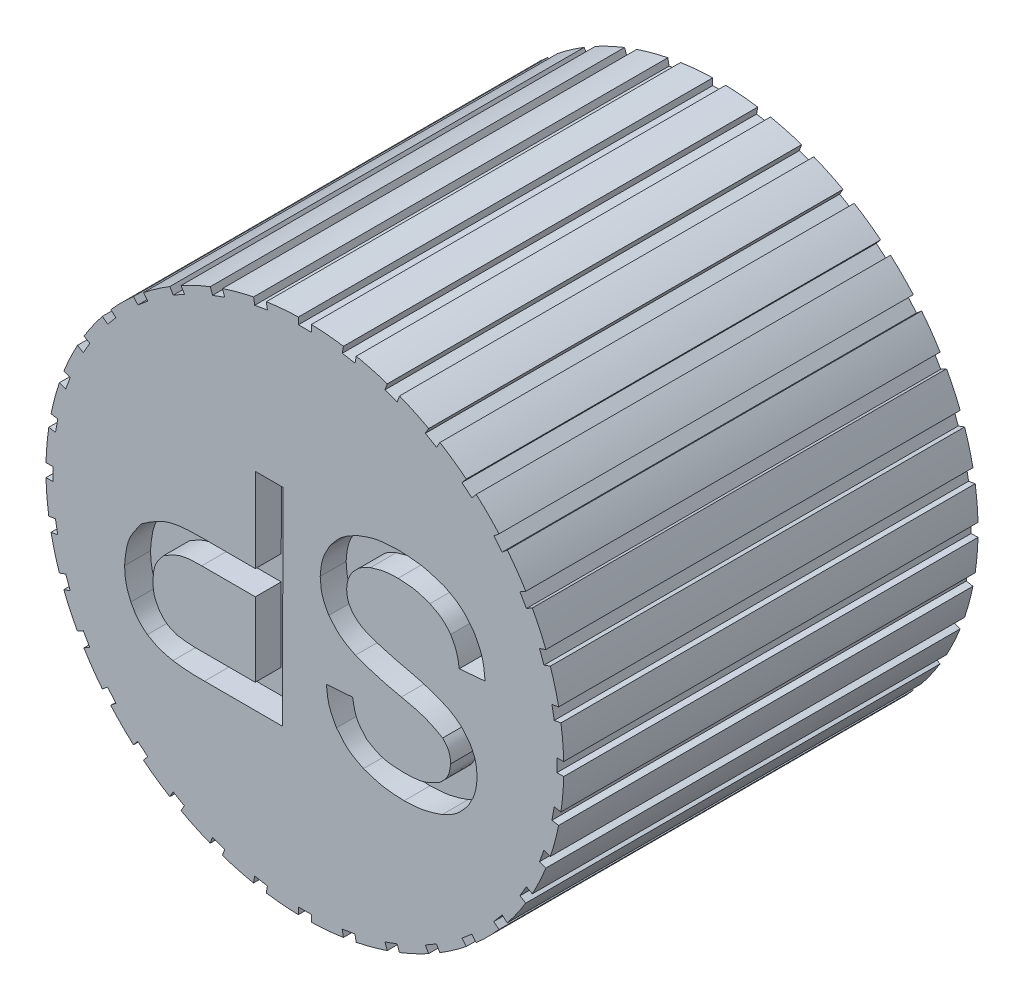
SolidWorks part; units mm, degrees
ref_plane "Front Plane" through (0, 0, 0) normal (0, 0, 1) x (1, 0, 0)
ref_plane "Top Plane" through (0, 0, 0) normal (0, 1, 0) x (1, 0, 0)
ref_plane "Right Plane" through (0, 0, 0) normal (1, 0, 0) x (0, 0, -1)
sketch "Sketch1" plane through (0, 0, 0) normal (0, 1, 0) x (1, 0, 0)
  line L0 (10, 0) -> (0, 0)
  line L1 (0, 0) -> (0, -16)
  line L2 (0, -16) -> (10, -16)
  line L3 (10, -16) -> (10, 0)
  line L4 (0, 0) -> (0, -16) construction
revolve "Revolve1" add sketch "Sketch1" angle 360 about L4
sketch "Sketch2" plane through (0, 0, 0) normal (0, 0, -1) x (-1, 0, 0)
  line L0 (3.183, 9.4799) -> (3.0936, 9.2344)
  line L1 (3.0936, 9.2344) -> (3.5632, 9.0635)
  line L2 (3.5632, 9.0635) -> (3.6526, 9.3091)
  arc A0 (3.6526, 9.3091) -> (3.183, 9.4799) centre (0, 0) ccw
extrude "Cut-Extrude1" cut sketch "Sketch2" against normal blind 16
sketch "Sketch3" plane through (0, 0, 0) normal (0, 0, -1) x (-1, 0, 0)
  line L0 (4.7808, 8.7832) -> (4.6502, 8.5569)
  line L1 (4.6502, 8.5569) -> (5.0829, 8.307)
  line L2 (5.0829, 8.307) -> (5.2136, 8.5334)
  arc A0 (5.2136, 8.5334) -> (4.7808, 8.7832) centre (0, 0) ccw
extrude "Cut-Extrude2" cut sketch "Sketch3" against normal blind 16
sketch "Sketch4" plane through (0, 0, 0) normal (0, 0, -1) x (-1, 0, 0)
  line L0 (6.2334, 7.8195) -> (6.0654, 7.6194)
  line L1 (6.0654, 7.6194) -> (6.4482, 7.2982)
  line L2 (6.4482, 7.2982) -> (6.6162, 7.4984)
  arc A0 (6.6162, 7.4984) -> (6.2334, 7.8195) centre (0, 0) ccw
extrude "Cut-Extrude3" cut sketch "Sketch4" against normal blind 16
sketch "Sketch5" plane through (0, 0, 0) normal (0, 0, -1) x (-1, 0, 0)
  line L0 (7.4965, 6.6183) -> (7.2963, 6.4504)
  line L1 (7.2963, 6.4504) -> (7.6176, 6.0676)
  line L2 (7.6176, 6.0676) -> (7.8178, 6.2356)
  arc A0 (7.8178, 6.2356) -> (7.4965, 6.6183) centre (0, 0) ccw
extrude "Cut-Extrude4" cut sketch "Sketch5" against normal blind 16
sketch "Sketch6" plane through (0, 0, 0) normal (0, 0, -1) x (-1, 0, 0)
  line L0 (8.5319, 5.216) -> (8.3056, 5.0854)
  line L1 (8.3056, 5.0854) -> (8.5554, 4.6526)
  line L2 (8.5554, 4.6526) -> (8.7818, 4.7833)
  arc A0 (8.7818, 4.7833) -> (8.5319, 5.216) centre (0, 0) ccw
extrude "Cut-Extrude5" cut sketch "Sketch6" against normal blind 16
sketch "Sketch7" plane through (0, 0, 0) normal (0, 0, -1) x (-1, 0, 0)
  line L0 (9.308, 3.6552) -> (9.0625, 3.5659)
  line L1 (9.0625, 3.5659) -> (9.2334, 3.0963)
  line L2 (9.2334, 3.0963) -> (9.479, 3.1857)
  arc A0 (9.479, 3.1857) -> (9.308, 3.6552) centre (0, 0) ccw
extrude "Cut-Extrude6" cut sketch "Sketch7" against normal blind 16
sketch "Sketch8" plane through (0, 0, 0) normal (0, 0, -1) x (-1, 0, 0)
  line L0 (9.8013, 1.9834) -> (9.544, 1.938)
  line L1 (9.544, 1.938) -> (9.6308, 1.4459)
  line L2 (9.6308, 1.4459) -> (9.8882, 1.4913)
  arc A0 (9.8882, 1.4913) -> (9.8013, 1.9834) centre (0, 0) ccw
extrude "Cut-Extrude7" cut sketch "Sketch8" against normal blind 16
sketch "Sketch9" plane through (0, 0, 0) normal (0, 0, -1) x (-1, 0, 0)
  line L0 (9.9968, 0.2513) -> (9.7356, 0.2513)
  line L1 (9.7356, 0.2513) -> (9.7356, -0.2484)
  line L2 (9.7356, -0.2484) -> (9.9969, -0.2484)
  arc A0 (9.9969, -0.2484) -> (9.9968, 0.2513) centre (0, 0) ccw
extrude "Cut-Extrude8" cut sketch "Sketch9" against normal blind 16
sketch "Sketch10" plane through (0, 0, 0) normal (0, 0, -1) x (-1, 0, 0)
  line L0 (9.8886, -1.4885) -> (9.6313, -1.4431)
  line L1 (9.6313, -1.4431) -> (9.5445, -1.9352)
  line L2 (9.5445, -1.9352) -> (9.8019, -1.9806)
  arc A0 (9.8019, -1.9806) -> (9.8886, -1.4885) centre (0, 0) ccw
extrude "Cut-Extrude9" cut sketch "Sketch10" against normal blind 16
sketch "Sketch11" plane through (0, 0, 0) normal (0, 0, -1) x (-1, 0, 0)
  line L0 (9.4799, -3.183) -> (9.2344, -3.0936)
  line L1 (9.2344, -3.0936) -> (9.0635, -3.5632)
  line L2 (9.0635, -3.5632) -> (9.3091, -3.6526)
  arc A0 (9.3091, -3.6526) -> (9.4799, -3.183) centre (0, 0) ccw
extrude "Cut-Extrude10" cut sketch "Sketch11" against normal blind 16
sketch "Sketch12" plane through (0, 0, 0) normal (0, 0, -1) x (-1, 0, 0)
  line L0 (8.7832, -4.7808) -> (8.5569, -4.6502)
  line L1 (8.5569, -4.6502) -> (8.307, -5.0829)
  line L2 (8.307, -5.0829) -> (8.5334, -5.2136)
  arc A0 (8.5334, -5.2136) -> (8.7832, -4.7808) centre (0, 0) ccw
extrude "Cut-Extrude11" cut sketch "Sketch12" against normal blind 16
sketch "Sketch13" plane through (0, 0, 0) normal (0, 0, -1) x (-1, 0, 0)
  line L0 (7.8195, -6.2334) -> (7.6194, -6.0654)
  line L1 (7.6194, -6.0654) -> (7.2982, -6.4482)
  line L2 (7.2982, -6.4482) -> (7.4984, -6.6162)
  arc A0 (7.4984, -6.6162) -> (7.8195, -6.2334) centre (0, 0) ccw
extrude "Cut-Extrude12" cut sketch "Sketch13" against normal blind 16
sketch "Sketch14" plane through (0, 0, 0) normal (0, 0, -1) x (-1, 0, 0)
  line L0 (6.6183, -7.4965) -> (6.4504, -7.2963)
  line L1 (6.4504, -7.2963) -> (6.0676, -7.6176)
  line L2 (6.0676, -7.6176) -> (6.2356, -7.8178)
  arc A0 (6.2356, -7.8178) -> (6.6183, -7.4965) centre (0, 0) ccw
extrude "Cut-Extrude13" cut sketch "Sketch14" against normal blind 16
sketch "Sketch15" plane through (0, 0, 0) normal (0, 0, -1) x (-1, 0, 0)
  line L0 (5.216, -8.5319) -> (5.0854, -8.3056)
  line L1 (5.0854, -8.3056) -> (4.6526, -8.5554)
  line L2 (4.6526, -8.5554) -> (4.7833, -8.7818)
  arc A0 (4.7833, -8.7818) -> (5.216, -8.5319) centre (0, 0) ccw
extrude "Cut-Extrude14" cut sketch "Sketch15" against normal blind 16
sketch "Sketch16" plane through (0, 0, 0) normal (0, 0, -1) x (-1, 0, 0)
  line L0 (3.6552, -9.308) -> (3.5659, -9.0625)
  line L1 (3.5659, -9.0625) -> (3.0963, -9.2334)
  line L2 (3.0963, -9.2334) -> (3.1857, -9.479)
  arc A0 (3.1857, -9.479) -> (3.6552, -9.308) centre (0, 0) ccw
extrude "Cut-Extrude15" cut sketch "Sketch16" against normal blind 16
sketch "Sketch17" plane through (0, 0, 0) normal (0, 0, -1) x (-1, 0, 0)
  line L0 (1.9834, -9.8013) -> (1.938, -9.544)
  line L1 (1.938, -9.544) -> (1.4459, -9.6308)
  line L2 (1.4459, -9.6308) -> (1.4913, -9.8882)
  arc A0 (1.4913, -9.8882) -> (1.9834, -9.8013) centre (0, 0) ccw
extrude "Cut-Extrude16" cut sketch "Sketch17" against normal blind 16
sketch "Sketch18" plane through (0, 0, 0) normal (0, 0, -1) x (-1, 0, 0)
  line L0 (0.2513, -9.9968) -> (0.2513, -9.7356)
  line L1 (0.2513, -9.7356) -> (-0.2484, -9.7356)
  line L2 (-0.2484, -9.7356) -> (-0.2484, -9.9969)
  arc A0 (-0.2484, -9.9969) -> (0.2513, -9.9968) centre (0, 0) ccw
extrude "Cut-Extrude17" cut sketch "Sketch18" against normal blind 16
sketch "Sketch19" plane through (0, 0, 0) normal (0, 0, -1) x (-1, 0, 0)
  line L0 (-1.4885, -9.8886) -> (-1.4431, -9.6313)
  line L1 (-1.4431, -9.6313) -> (-1.9352, -9.5445)
  line L2 (-1.9352, -9.5445) -> (-1.9806, -9.8019)
  arc A0 (-1.9806, -9.8019) -> (-1.4885, -9.8886) centre (0, 0) ccw
extrude "Cut-Extrude18" cut sketch "Sketch19" against normal blind 16
sketch "Sketch20" plane through (0, 0, 0) normal (0, 0, -1) x (-1, 0, 0)
  line L0 (-3.183, -9.4799) -> (-3.0936, -9.2344)
  line L1 (-3.0936, -9.2344) -> (-3.5632, -9.0635)
  line L2 (-3.5632, -9.0635) -> (-3.6526, -9.3091)
  arc A0 (-3.6526, -9.3091) -> (-3.183, -9.4799) centre (0, 0) ccw
extrude "Cut-Extrude19" cut sketch "Sketch20" against normal blind 16
sketch "Sketch21" plane through (0, 0, 0) normal (0, 0, -1) x (-1, 0, 0)
  line L0 (-4.7808, -8.7832) -> (-4.6502, -8.5569)
  line L1 (-4.6502, -8.5569) -> (-5.0829, -8.307)
  line L2 (-5.0829, -8.307) -> (-5.2136, -8.5334)
  arc A0 (-5.2136, -8.5334) -> (-4.7808, -8.7832) centre (0, 0) ccw
extrude "Cut-Extrude20" cut sketch "Sketch21" against normal blind 16
sketch "Sketch22" plane through (0, 0, 0) normal (0, 0, -1) x (-1, 0, 0)
  line L0 (-6.2334, -7.8195) -> (-6.0654, -7.6194)
  line L1 (-6.0654, -7.6194) -> (-6.4482, -7.2982)
  line L2 (-6.4482, -7.2982) -> (-6.6162, -7.4984)
  arc A0 (-6.6162, -7.4984) -> (-6.2334, -7.8195) centre (0, 0) ccw
extrude "Cut-Extrude21" cut sketch "Sketch22" against normal blind 16
sketch "Sketch23" plane through (0, 0, 0) normal (0, 0, -1) x (-1, 0, 0)
  line L0 (-7.4965, -6.6183) -> (-7.2963, -6.4504)
  line L1 (-7.2963, -6.4504) -> (-7.6176, -6.0676)
  line L2 (-7.6176, -6.0676) -> (-7.8178, -6.2356)
  arc A0 (-7.8178, -6.2356) -> (-7.4965, -6.6183) centre (0, 0) ccw
extrude "Cut-Extrude22" cut sketch "Sketch23" against normal blind 16
sketch "Sketch24" plane through (0, 0, 0) normal (0, 0, -1) x (-1, 0, 0)
  line L0 (-8.5319, -5.216) -> (-8.3056, -5.0854)
  line L1 (-8.3056, -5.0854) -> (-8.5554, -4.6526)
  line L2 (-8.5554, -4.6526) -> (-8.7818, -4.7833)
  arc A0 (-8.7818, -4.7833) -> (-8.5319, -5.216) centre (0, 0) ccw
extrude "Cut-Extrude23" cut sketch "Sketch24" against normal blind 16
sketch "Sketch25" plane through (0, 0, 0) normal (0, 0, -1) x (-1, 0, 0)
  line L0 (-9.308, -3.6552) -> (-9.0625, -3.5659)
  line L1 (-9.0625, -3.5659) -> (-9.2334, -3.0963)
  line L2 (-9.2334, -3.0963) -> (-9.479, -3.1857)
  arc A0 (-9.479, -3.1857) -> (-9.308, -3.6552) centre (0, 0) ccw
extrude "Cut-Extrude24" cut sketch "Sketch25" against normal blind 16
sketch "Sketch26" plane through (0, 0, 0) normal (0, 0, -1) x (-1, 0, 0)
  line L0 (-9.8013, -1.9834) -> (-9.544, -1.938)
  line L1 (-9.544, -1.938) -> (-9.6308, -1.4459)
  line L2 (-9.6308, -1.4459) -> (-9.8882, -1.4913)
  arc A0 (-9.8882, -1.4913) -> (-9.8013, -1.9834) centre (0, 0) ccw
extrude "Cut-Extrude25" cut sketch "Sketch26" against normal blind 16
sketch "Sketch27" plane through (0, 0, 0) normal (0, 0, -1) x (-1, 0, 0)
  line L0 (-9.9968, -0.2513) -> (-9.7356, -0.2513)
  line L1 (-9.7356, -0.2513) -> (-9.7356, 0.2484)
  line L2 (-9.7356, 0.2484) -> (-9.9969, 0.2484)
  arc A0 (-9.9969, 0.2484) -> (-9.9968, -0.2513) centre (0, 0) ccw
extrude "Cut-Extrude26" cut sketch "Sketch27" against normal blind 16
sketch "Sketch28" plane through (0, 0, 0) normal (0, 0, -1) x (-1, 0, 0)
  line L0 (-9.8886, 1.4885) -> (-9.6313, 1.4431)
  line L1 (-9.6313, 1.4431) -> (-9.5445, 1.9352)
  line L2 (-9.5445, 1.9352) -> (-9.8019, 1.9806)
  arc A0 (-9.8019, 1.9806) -> (-9.8886, 1.4885) centre (0, 0) ccw
extrude "Cut-Extrude27" cut sketch "Sketch28" against normal blind 16
sketch "Sketch29" plane through (0, 0, 0) normal (0, 0, -1) x (-1, 0, 0)
  line L0 (-9.4799, 3.183) -> (-9.2344, 3.0936)
  line L1 (-9.2344, 3.0936) -> (-9.0635, 3.5632)
  line L2 (-9.0635, 3.5632) -> (-9.3091, 3.6526)
  arc A0 (-9.3091, 3.6526) -> (-9.4799, 3.183) centre (0, 0) ccw
extrude "Cut-Extrude28" cut sketch "Sketch29" against normal blind 16
sketch "Sketch30" plane through (0, 0, 0) normal (0, 0, -1) x (-1, 0, 0)
  line L0 (-8.7832, 4.7808) -> (-8.5569, 4.6502)
  line L1 (-8.5569, 4.6502) -> (-8.307, 5.0829)
  line L2 (-8.307, 5.0829) -> (-8.5334, 5.2136)
  arc A0 (-8.5334, 5.2136) -> (-8.7832, 4.7808) centre (0, 0) ccw
extrude "Cut-Extrude29" cut sketch "Sketch30" against normal blind 16
sketch "Sketch31" plane through (0, 0, 0) normal (0, 0, -1) x (-1, 0, 0)
  line L0 (-7.8195, 6.2334) -> (-7.6194, 6.0654)
  line L1 (-7.6194, 6.0654) -> (-7.2982, 6.4482)
  line L2 (-7.2982, 6.4482) -> (-7.4984, 6.6162)
  arc A0 (-7.4984, 6.6162) -> (-7.8195, 6.2334) centre (0, 0) ccw
extrude "Cut-Extrude30" cut sketch "Sketch31" against normal blind 16
sketch "Sketch32" plane through (0, 0, 0) normal (0, 0, -1) x (-1, 0, 0)
  line L0 (-6.6183, 7.4965) -> (-6.4504, 7.2963)
  line L1 (-6.4504, 7.2963) -> (-6.0676, 7.6176)
  line L2 (-6.0676, 7.6176) -> (-6.2356, 7.8178)
  arc A0 (-6.2356, 7.8178) -> (-6.6183, 7.4965) centre (0, 0) ccw
extrude "Cut-Extrude31" cut sketch "Sketch32" against normal blind 16
sketch "Sketch33" plane through (0, 0, 0) normal (0, 0, -1) x (-1, 0, 0)
  line L0 (-5.216, 8.5319) -> (-5.0854, 8.3056)
  line L1 (-5.0854, 8.3056) -> (-4.6526, 8.5554)
  line L2 (-4.6526, 8.5554) -> (-4.7833, 8.7818)
  arc A0 (-4.7833, 8.7818) -> (-5.216, 8.5319) centre (0, 0) ccw
extrude "Cut-Extrude32" cut sketch "Sketch33" against normal blind 16
sketch "Sketch34" plane through (0, 0, 0) normal (0, 0, -1) x (-1, 0, 0)
  line L0 (-3.6552, 9.308) -> (-3.5659, 9.0625)
  line L1 (-3.5659, 9.0625) -> (-3.0963, 9.2334)
  line L2 (-3.0963, 9.2334) -> (-3.1857, 9.479)
  arc A0 (-3.1857, 9.479) -> (-3.6552, 9.308) centre (0, 0) ccw
extrude "Cut-Extrude33" cut sketch "Sketch34" against normal blind 16
sketch "Sketch35" plane through (0, 0, 0) normal (0, 0, -1) x (-1, 0, 0)
  line L0 (-1.9834, 9.8013) -> (-1.938, 9.544)
  line L1 (-1.938, 9.544) -> (-1.4459, 9.6308)
  line L2 (-1.4459, 9.6308) -> (-1.4913, 9.8882)
  arc A0 (-1.4913, 9.8882) -> (-1.9834, 9.8013) centre (0, 0) ccw
extrude "Cut-Extrude34" cut sketch "Sketch35" against normal blind 16
sketch "Sketch36" plane through (0, 0, 0) normal (0, 0, -1) x (-1, 0, 0)
  line L0 (-0.2513, 9.9968) -> (-0.2513, 9.7356)
  line L1 (-0.2513, 9.7356) -> (0.2484, 9.7356)
  line L2 (0.2484, 9.7356) -> (0.2484, 9.9969)
  arc A0 (0.2484, 9.9969) -> (-0.2513, 9.9968) centre (0, 0) ccw
extrude "Cut-Extrude35" cut sketch "Sketch36" against normal blind 16
sketch "Sketch37" plane through (0, 0, 0) normal (0, 0, -1) x (-1, 0, 0)
  line L0 (1.4885, 9.8886) -> (1.4431, 9.6313)
  line L1 (1.4431, 9.6313) -> (1.9352, 9.5445)
  line L2 (1.9352, 9.5445) -> (1.9806, 9.8019)
  arc A0 (1.9806, 9.8019) -> (1.4885, 9.8886) centre (0, 0) ccw
extrude "Cut-Extrude36" cut sketch "Sketch37" against normal blind 16
hole_wizard "Ø6.0 (6) Diameter Hole1" positions "Sketch39" profile "Sketch38" hole size "Ø6.0" standard "ANSI Metric"
sketch "Sketch39" plane through (0, 0, 0) normal (0, 0, -1) x (-1, 0, 0)
  point P0 (0, 0)
sketch "Sketch38" plane through (0, 0, 0) normal (1, 0, 0) x (0, 1, 0)
  line L0 (0, 0) -> (0, 14)
  line L1 (0, 14) -> (3, 14)
  line L2 (3, 14) -> (3, 0)
  line L5 (3, 0) -> (0, 0)
  line L10 (0, 14) -> (-3, 14) construction
  line L11 (0, -6.35) -> (0, 107.95) construction
  dimension "Hole Dia." = 6
  dimension "Hole Depth" = 14
  dimension "Drill Angle" = 180
sketch "Sketch40" plane through (0, 0, 14) normal (0, 0, -1) x (-1, 0, 0)
  line L0 (1.9843, 2.25) -> (-1.9843, 2.25)
  arc A0 (-1.9843, 2.25) -> (1.9843, 2.25) centre (0, 0) cw
extrude "Boss-Extrude1" add sketch "Sketch40" along normal blind 11.5
ref_plane "Plane1" through (0, 0, 13) normal (0, 0, 1) x (1, 0, 0)
sketch "Sketch41" plane through (0, 0, 13) normal (0, 0, 1) x (1, 0, 0)
  line L0 (-0.8576, -3.9992) -> (-3.8753, -3.9965)
  line L1 (-3.9639, 0.7512) -> (-1.912, 0.7493)
  line L2 (-1.912, 0.7493) -> (-1.9091, 4.0017)
  line L3 (-1.9091, 4.0017) -> (-0.8504, 4.0008)
  line L4 (-0.8504, 4.0008) -> (-0.8576, -3.9992)
  arc A0 (-3.8753, -3.9965) -> (-5.0922, -3.919) centre (-4.0199, 3.3272) cw
  spline S0 degree 3 poles (-5.0922, -3.919) (-5.1616, -3.9049) (-5.3004, -3.8767) (-5.5066, -3.8244) (-5.7064, -3.7501) (-5.8958, -3.6521) (-6.0183, -3.5803) (-6.0796, -3.5443) knots 0 0 0 0 0.199818 0.399437 0.599469 0.799548 1 1 1 1
  spline S1 degree 3 poles (-6.0796, -3.5443) (-6.1086, -3.5207) (-6.1667, -3.4734) (-6.2524, -3.4009) (-6.3352, -3.325) (-6.4137, -3.2443) (-6.4854, -3.1572) (-6.5502, -3.0647) (-6.6097, -2.9687) (-6.6658, -2.8706) (-6.702, -2.8046) (-6.7201, -2.7716) knots 0 0 0 0 0.110867 0.221625 0.332283 0.443112 0.554485 0.665741 0.777135 0.888564 1 1 1 1
  spline S2 degree 3 poles (-6.7201, -2.7716) (-6.7487, -2.7023) (-6.8058, -2.5636) (-6.8806, -2.351) (-6.929, -2.1304) (-6.9512, -1.9055) (-6.9584, -1.7552) (-6.9619, -1.68) knots 0 0 0 0 0.199722 0.399196 0.599258 0.799452 1 1 1 1
  spline S3 degree 3 poles (-6.9619, -1.68) (-6.955, -1.59) (-6.941, -1.4104) (-6.9087, -1.1429) (-6.8531, -0.8799) (-6.7591, -0.6274) (-6.627, -0.392) (-6.4739, -0.1691) (-6.3653, -0.0253) (-6.311, 0.0466) knots 0 0 0 0 0.143507 0.2866 0.428442 0.570098 0.713348 0.856629 1 1 1 1
  spline S4 degree 3 poles (-6.311, 0.0466) (-6.2341, 0.1) (-6.0804, 0.2069) (-5.8446, 0.3596) (-5.599, 0.4948) (-5.3415, 0.6024) (-5.0734, 0.6736) (-4.7996, 0.7162) (-4.5222, 0.7387) (-4.2432, 0.7482) (-4.057, 0.7502) (-3.9639, 0.7512) knots 0 0 0 0 0.111905 0.223719 0.335717 0.446572 0.556279 0.666369 0.777426 0.888707 1 1 1 1
extrude "Cut-Extrude37" cut sketch "Sketch41" against normal blind 1 from surface at 3 starting at face at (0, 0, 16)
ref_plane "Plane2" through (0, 0, 18) normal (0, 0, -1) x (0, 1, 0)
sketch "Sketch42" plane through (0, 0, 18) normal (0, 0, -1) x (0, 1, 0)
  line L0 (-3.0524, -3.9618) -> (-3.0542, -1.9154)
  line L1 (-3.0542, -1.9154) -> (-0.1947, -1.9129)
  line L2 (-0.1947, -1.9129) -> (-0.1929, -3.9811)
  arc A0 (-2.9806, -4.9495) -> (-3.0524, -3.9618) centre (1.5318, -4.1249) cw
  spline S0 degree 3 poles (-2.5079, -5.6175) (-2.5509, -5.5817) (-2.6366, -5.5102) (-2.7565, -5.3938) (-2.853, -5.2575) (-2.9226, -5.1061) (-2.9612, -5.0018) (-2.9806, -4.9495) knots 0 0 0 0 0.201652 0.401782 0.599697 0.799039 1 1 1 1
  spline S1 degree 3 poles (-0.1929, -3.9811) (-0.1935, -4.038) (-0.1946, -4.152) (-0.1998, -4.3227) (-0.2123, -4.4925) (-0.2357, -4.6604) (-0.2742, -4.8251) (-0.3319, -4.985) (-0.4044, -5.1397) (-0.4868, -5.2902) (-0.5446, -5.389) (-0.5736, -5.4384) knots 0 0 0 0 0.111441 0.222872 0.33409 0.444372 0.554109 0.664377 0.776028 0.888003 1 1 1 1
  spline S2 degree 3 poles (-0.5736, -5.4384) (-0.6071, -5.4674) (-0.674, -5.5252) (-0.7772, -5.6089) (-0.8853, -5.6855) (-1.0004, -5.7508) (-1.1239, -5.7987) (-1.2527, -5.8299) (-1.3839, -5.8496) (-1.5159, -5.8619) (-1.6041, -5.8676) (-1.6482, -5.8705) knots 0 0 0 0 0.111394 0.222725 0.334165 0.444661 0.554941 0.66642 0.777581 0.888729 1 1 1 1
  spline S3 degree 3 poles (-1.6482, -5.8705) (-1.682, -5.8686) (-1.7495, -5.8649) (-1.8505, -5.8572) (-1.9509, -5.8451) (-2.0498, -5.8265) (-2.1464, -5.7988) (-2.2399, -5.7612) (-2.3309, -5.7169) (-2.42, -5.6683) (-2.4786, -5.6344) (-2.5079, -5.6175) knots 0 0 0 0 0.111519 0.223027 0.33434 0.444774 0.554758 0.665246 0.776716 0.88835 1 1 1 1
extrude "Boss-Extrude2" add sketch "Sketch42" against normal blind 1 from surface at 3 starting at face at (-3.9973, -0.7319, 15)
sketch "Sketch43" plane through (0, 0, 13) normal (0, 0, 1) x (1, 0, 0)
  line L0 (0.8306, -1.747) -> (1.8457, -1.6715)
  line L1 (6.9617, 1.4235) -> (5.963, 1.3371)
  arc A0 (2.5518, 0.6962) -> (3.9757, 0.3048) centre (7.0683, 14.3396) ccw
  arc A1 (3.9757, 0.3048) -> (5.5196, -0.1959) centre (2.4936, -6.8957) cw
  arc A2 (3.7265, -0.7264) -> (1.9562, -0.2146) centre (5.8003, 9.7643) cw
  spline S0 degree 3 poles (5.963, 1.3371) (5.9526, 1.4061) (5.9319, 1.544) (5.8904, 1.7493) (5.8256, 1.9491) (5.735, 2.1386) (5.6675, 2.2611) (5.6337, 2.3224) knots 0 0 0 0 0.199817 0.399408 0.599425 0.799489 1 1 1 1
  spline S1 degree 3 poles (5.6337, 2.3224) (5.6094, 2.3516) (5.5608, 2.41) (5.486, 2.496) (5.4075, 2.5786) (5.3235, 2.6562) (5.2322, 2.7256) (5.1354, 2.7873) (5.0352, 2.8432) (4.9328, 2.8952) (4.8638, 2.9285) (4.8294, 2.9452) knots 0 0 0 0 0.11079 0.22144 0.331965 0.442711 0.554155 0.665473 0.776952 0.888472 1 1 1 1
  spline S2 degree 3 poles (4.8294, 2.9452) (4.7856, 2.9611) (4.6981, 2.9928) (4.5662, 3.0384) (4.433, 3.0798) (4.2977, 3.115) (4.1602, 3.1413) (4.0212, 3.159) (3.8817, 3.1706) (3.7418, 3.1782) (3.6484, 3.1818) (3.6018, 3.1837) knots 0 0 0 0 0.110954 0.221835 0.332653 0.443579 0.554858 0.666067 0.777362 0.888679 1 1 1 1
  spline S3 degree 3 poles (3.6018, 3.1837) (3.5614, 3.1825) (3.4808, 3.1801) (3.3599, 3.175) (3.2392, 3.1667) (3.1188, 3.1538) (2.9992, 3.1344) (2.8808, 3.1078) (2.7638, 3.0762) (2.6476, 3.0412) (2.5706, 3.0168) (2.532, 3.0045) knots 0 0 0 0 0.11102 0.22199 0.332916 0.443916 0.555146 0.666287 0.77751 0.888753 1 1 1 1
  spline S4 degree 3 poles (2.532, 3.0045) (2.4792, 2.9817) (2.3737, 2.9359) (2.2199, 2.8577) (2.0786, 2.7588) (1.9554, 2.6389) (1.8793, 2.5539) (1.8413, 2.5113) knots 0 0 0 0 0.20097 0.401435 0.601625 0.800606 1 1 1 1
  spline S5 degree 3 poles (1.8413, 2.5113) (1.8269, 2.4882) (1.7981, 2.442) (1.7564, 2.3717) (1.7181, 2.2997) (1.6849, 2.2256) (1.6593, 2.1488) (1.6415, 2.0696) (1.6293, 1.9892) (1.6208, 1.908) (1.6164, 1.8538) (1.6142, 1.8267) knots 0 0 0 0 0.111566 0.223105 0.334646 0.445332 0.555378 0.665775 0.777052 0.88852 1 1 1 1
  spline S6 degree 3 poles (1.6142, 1.8267) (1.616, 1.8005) (1.6196, 1.7482) (1.6269, 1.6699) (1.6378, 1.5922) (1.6544, 1.5157) (1.6787, 1.4416) (1.7109, 1.3706) (1.7484, 1.3019) (1.7893, 1.2349) (1.8177, 1.1909) (1.8319, 1.1689) knots 0 0 0 0 0.111558 0.223072 0.33467 0.445561 0.555613 0.665938 0.777161 0.888574 1 1 1 1
  spline S7 degree 3 poles (1.8319, 1.1689) (1.8545, 1.1461) (1.8998, 1.1005) (1.9692, 1.0336) (2.0414, 0.9698) (2.1178, 0.9106) (2.1994, 0.8585) (2.2849, 0.8124) (2.3727, 0.7711) (2.4619, 0.7329) (2.5218, 0.7084) (2.5518, 0.6962) knots 0 0 0 0 0.110793 0.221445 0.331976 0.442716 0.554139 0.665488 0.776967 0.88848 1 1 1 1
  spline S8 degree 3 poles (5.5196, -0.1959) (5.5563, -0.2172) (5.6295, -0.2595) (5.7383, -0.325) (5.8446, -0.3944) (5.9471, -0.4697) (6.0438, -0.5527) (6.1329, -0.6439) (6.2163, -0.7404) (6.2956, -0.8402) (6.3472, -0.9078) (6.373, -0.9416) knots 0 0 0 0 0.110936 0.221777 0.332532 0.443436 0.554783 0.665934 0.777258 0.888625 1 1 1 1
  spline S9 degree 3 poles (6.373, -0.9416) (6.4058, -1.0034) (6.4714, -1.1267) (6.5578, -1.3179) (6.6142, -1.5202) (6.6403, -1.7284) (6.6488, -1.8679) (6.6531, -1.9378) knots 0 0 0 0 0.200442 0.400254 0.599543 0.799433 1 1 1 1
  spline S10 degree 3 poles (6.6531, -1.9378) (6.6471, -2.0176) (6.6351, -2.177) (6.6012, -2.4147) (6.5308, -2.6446) (6.4264, -2.8608) (6.3477, -3) (6.3083, -3.0698) knots 0 0 0 0 0.200463 0.400277 0.599557 0.799395 1 1 1 1
  spline S11 degree 3 poles (6.3083, -3.0698) (6.2783, -3.1078) (6.2182, -3.1837) (6.1256, -3.2956) (6.0283, -3.4027) (5.9243, -3.5025) (5.8112, -3.5914) (5.6903, -3.6697) (5.564, -3.7404) (5.4344, -3.8057) (5.3471, -3.8474) (5.3035, -3.8683) knots 0 0 0 0 0.111631 0.223251 0.334625 0.44507 0.555082 0.665557 0.776902 0.888446 1 1 1 1
  spline S12 degree 3 poles (5.3035, -3.8683) (5.251, -3.8864) (5.146, -3.9226) (4.9877, -3.9746) (4.828, -4.0218) (4.6661, -4.0619) (4.5018, -4.0918) (4.3358, -4.112) (4.1693, -4.1252) (4.0023, -4.1337) (3.891, -4.1378) (3.8353, -4.1399) knots 0 0 0 0 0.110969 0.221873 0.33272 0.443664 0.554927 0.666125 0.777402 0.888699 1 1 1 1
  spline S13 degree 3 poles (3.8353, -4.1399) (3.776, -4.1378) (3.6573, -4.1337) (3.4795, -4.1252) (3.302, -4.1117) (3.125, -4.0908) (2.9494, -4.0595) (2.776, -4.0168) (2.6049, -3.9662) (2.4353, -3.9104) (2.3229, -3.8714) (2.2667, -3.852) knots 0 0 0 0 0.111007 0.221956 0.332855 0.443841 0.555089 0.666232 0.777471 0.888733 1 1 1 1
  spline S14 degree 3 poles (2.2667, -3.852) (2.2213, -3.8296) (2.1305, -3.7849) (1.9959, -3.715) (1.8646, -3.6397) (1.7388, -3.5565) (1.6213, -3.4624) (1.5133, -3.3573) (1.4122, -3.2448) (1.316, -3.1274) (1.2536, -3.0477) (1.2224, -3.0079) knots 0 0 0 0 0.11152 0.223024 0.334429 0.445018 0.555115 0.665589 0.776922 0.888456 1 1 1 1
  spline S15 degree 3 poles (1.2224, -3.0079) (1.179, -2.93) (1.0924, -2.7743) (0.9772, -2.533) (0.8984, -2.2771) (0.8565, -2.0131) (0.8393, -1.8358) (0.8306, -1.747) knots 0 0 0 0 0.200478 0.400337 0.599651 0.799529 1 1 1 1
  spline S16 degree 3 poles (1.8457, -1.6715) (1.8535, -1.7192) (1.869, -1.8145) (1.8958, -1.9567) (1.9301, -2.0976) (1.9754, -2.2353) (2.0365, -2.3667) (2.1146, -2.4887) (2.2036, -2.603) (2.2996, -2.7119) (2.3656, -2.7826) (2.3986, -2.818) knots 0 0 0 0 0.111175 0.222233 0.333273 0.444721 0.555342 0.66595 0.777329 0.888641 1 1 1 1
  spline S17 degree 3 poles (2.3986, -2.818) (2.459, -2.8539) (2.5798, -2.9256) (2.7656, -3.0251) (2.9598, -3.1066) (3.1634, -3.1592) (3.3715, -3.1875) (3.5816, -3.2008) (3.7222, -3.2047) (3.7925, -3.2067) knots 0 0 0 0 0.143206 0.286332 0.429271 0.571216 0.713489 0.856647 1 1 1 1
  spline S18 degree 3 poles (3.7925, -3.2067) (3.8625, -3.2057) (4.0026, -3.2038) (4.212, -3.194) (4.4199, -3.1701) (4.624, -3.1238) (4.8201, -3.0495) (5.0084, -2.9569) (5.1312, -2.8896) (5.1925, -2.856) knots 0 0 0 0 0.14333 0.286525 0.428919 0.570897 0.713627 0.856782 1 1 1 1
  spline S19 degree 3 poles (5.1925, -2.856) (5.2271, -2.8237) (5.2962, -2.7592) (5.3946, -2.6579) (5.4817, -2.547) (5.548, -2.4221) (5.5889, -2.2867) (5.6145, -2.1477) (5.6265, -2.0545) (5.6326, -2.0078) knots 0 0 0 0 0.143802 0.287183 0.429026 0.570787 0.71414 0.856971 1 1 1 1
  spline S20 degree 3 poles (5.6326, -2.0078) (5.6292, -1.9697) (5.6225, -1.8937) (5.6069, -1.7807) (5.5799, -1.6699) (5.5342, -1.5651) (5.4709, -1.4702) (5.3986, -1.3823) (5.3477, -1.3262) (5.3222, -1.2981) knots 0 0 0 0 0.143772 0.287137 0.429296 0.571647 0.71477 0.857265 1 1 1 1
  spline S21 degree 3 poles (5.3222, -1.2981) (5.2671, -1.2674) (5.1571, -1.2059) (4.9904, -1.117) (4.8199, -1.0355) (4.6445, -0.9642) (4.4648, -0.9038) (4.2821, -0.8519) (4.0978, -0.8065) (3.9124, -0.7654) (3.7885, -0.7394) (3.7265, -0.7264) knots 0 0 0 0 0.110911 0.221702 0.33239 0.443259 0.554573 0.665882 0.777245 0.888621 1 1 1 1
  spline S22 degree 3 poles (1.9562, -0.2146) (1.877, -0.1743) (1.7189, -0.0939) (1.489, 0.0402) (1.2784, 0.2037) (1.0954, 0.3972) (0.9822, 0.5338) (0.9255, 0.6022) knots 0 0 0 0 0.200431 0.400336 0.599684 0.799515 1 1 1 1
  spline S23 degree 3 poles (0.9255, 0.6022) (0.9037, 0.6412) (0.86, 0.7192) (0.797, 0.8375) (0.7396, 0.9582) (0.6907, 1.082) (0.654, 1.2096) (0.629, 1.3403) (0.6125, 1.4729) (0.6017, 1.6064) (0.5963, 1.6956) (0.5936, 1.7403) knots 0 0 0 0 0.111606 0.223204 0.33456 0.445014 0.555046 0.665531 0.776882 0.888436 1 1 1 1
  spline S24 degree 3 poles (0.5936, 1.7403) (0.6002, 1.8251) (0.6132, 1.9945) (0.6495, 2.2469) (0.7245, 2.4911) (0.8352, 2.7209) (0.9186, 2.869) (0.9603, 2.9432) knots 0 0 0 0 0.200474 0.400287 0.599555 0.799441 1 1 1 1
  spline S25 degree 3 poles (0.9603, 2.9432) (0.9917, 2.9837) (1.0543, 3.0647) (1.1507, 3.1841) (1.2522, 3.2994) (1.3611, 3.4082) (1.4799, 3.5067) (1.607, 3.5947) (1.7393, 3.6746) (1.8747, 3.749) (1.966, 3.7969) (2.0116, 3.8208) knots 0 0 0 0 0.110822 0.221512 0.332084 0.442866 0.554296 0.665564 0.77701 0.888501 1 1 1 1
  spline S26 degree 3 poles (2.0116, 3.8208) (2.0664, 3.8417) (2.1758, 3.8833) (2.341, 3.9431) (2.508, 3.9975) (2.6778, 4.0438) (2.8506, 4.0782) (3.0255, 4.1014) (3.2011, 4.1165) (3.3773, 4.1262) (3.4948, 4.1309) (3.5535, 4.1332) knots 0 0 0 0 0.110939 0.2218 0.332592 0.443502 0.554797 0.666012 0.777324 0.888659 1 1 1 1
  spline S27 degree 3 poles (3.5535, 4.1332) (3.6223, 4.1314) (3.7597, 4.1278) (3.9658, 4.1197) (4.1716, 4.1059) (4.3768, 4.0837) (4.5807, 4.0497) (4.7819, 4.0022) (4.9806, 3.9451) (5.1774, 3.8817) (5.3079, 3.8373) (5.3731, 3.8151) knots 0 0 0 0 0.111016 0.221976 0.332887 0.443881 0.555126 0.666255 0.777485 0.88874 1 1 1 1
  spline S28 degree 3 poles (5.3731, 3.8151) (5.4233, 3.7895) (5.5235, 3.7384) (5.6723, 3.6586) (5.8171, 3.5728) (5.9557, 3.4783) (6.0848, 3.3718) (6.2036, 3.2535) (6.3148, 3.1271) (6.4206, 2.9956) (6.4894, 2.9064) (6.5237, 2.8618) knots 0 0 0 0 0.11153 0.223048 0.334406 0.444939 0.555035 0.665542 0.776899 0.888444 1 1 1 1
  spline S29 degree 3 poles (6.5237, 2.8618) (6.551, 2.8127) (6.6055, 2.7144) (6.6843, 2.5654) (6.7569, 2.4133) (6.8203, 2.2567) (6.8694, 2.0946) (6.9044, 1.9287) (6.9291, 1.761) (6.9471, 1.5924) (6.9568, 1.4798) (6.9617, 1.4235) knots 0 0 0 0 0.110862 0.221604 0.332242 0.44308 0.554484 0.665702 0.777105 0.888548 1 1 1 1
extrude "Cut-Extrude38" cut sketch "Sketch43" against normal blind 1 from surface at 3 starting at face at (-3.9973, -0.7319, 16)
